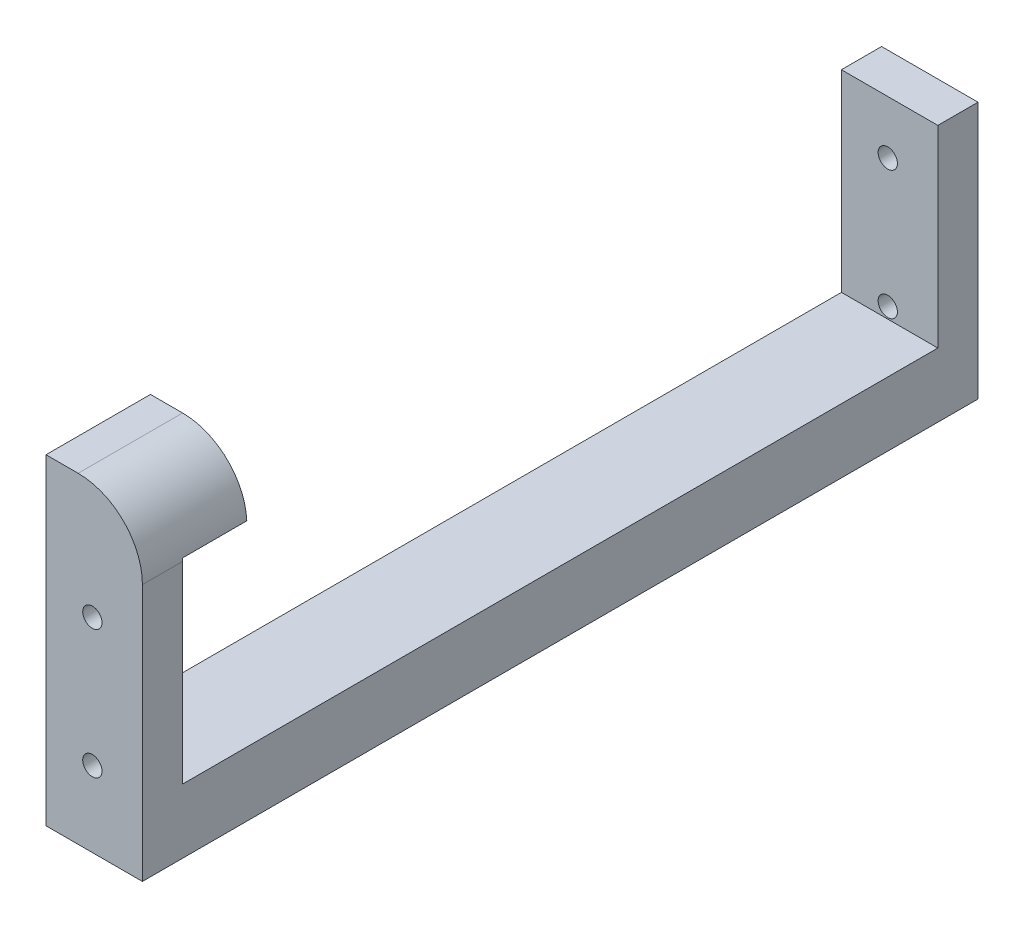
SolidWorks part; units mm, degrees
ref_plane "Front Plane" through (0, 0, 0) normal (0, 0, 1) x (1, 0, 0)
ref_plane "Top Plane" through (0, 0, 0) normal (0, 1, 0) x (1, 0, 0)
ref_plane "Right Plane" through (0, 0, 0) normal (1, 0, 0) x (0, 0, -1)
sketch "Sketch1" plane through (0, 0, 0) normal (0, 0, 1) x (1, 0, 0)
  line L1 (-7.5, 25) -> (7.5, 25)
  line L2 (-7.5, 25) -> (-7.5, -15)
  line L3 (-7.5, -15) -> (7.5, -15)
  line L4 (7.5, 25) -> (7.5, -15)
  dimension "D1" = 15
  dimension "D2" = 40
  dimension "D3" = 7.5
  dimension "D4" = 15
extrude "Boss-Extrude1" add sketch "Sketch1" along normal blind 130
sketch "Sketch2" plane through (0, 25, 0) normal (0, 1, 0) x (1, 0, 0)
  line L0 (-7.5, -130) -> (-7.5, 0) construction
  line L1 (-7.5, -6.25) -> (7.5, -6.25)
  line L2 (-7.5, -6.25) -> (-7.5, -123.75)
  line L3 (-7.5, -123.75) -> (7.5, -123.75)
  line L4 (7.5, -6.25) -> (7.5, -123.75)
  line L5 (7.5, -130) -> (7.5, 0) construction
  line L6 (7.5, -130) -> (-7.5, -130) construction
  dimension "1" = 117.5
  dimension "6.25" = 6.25
extrude "Cut-Extrude1" cut sketch "Sketch2" against normal blind 30
sketch "Sketch3" plane through (0, 0, 0) normal (0, 0, -1) x (-1, 0, 0)
  circle A0 centre (0.2894, 16.7166) radius 1.5
  circle A1 centre (0.2894, -3.2834) radius 1.5
  dimension "D2" = 3
  dimension "D3" = 3
  dimension "D1" = 20
extrude "Cut-Extrude2" cut sketch "Sketch3" against normal through all both and the other way through all
sketch "Sketch4" plane through (0, 25, 0) normal (0, 1, 0) x (1, 0, 0)
  line L1 (-7.5, 0) -> (7.5, 0)
  line L2 (-7.5, 0) -> (-7.5, -6.25)
  line L3 (-7.5, -6.25) -> (7.5, -6.25)
  line L4 (7.5, 0) -> (7.5, -6.25)
  line L5 (-7.5, -123.75) -> (7.5, -123.75)
  line L6 (-7.5, -123.75) -> (-7.5, -130)
  line L7 (-7.5, -130) -> (7.5, -130)
  line L8 (7.5, -123.75) -> (7.5, -130)
extrude "Boss-Extrude2" add sketch "Sketch4" along normal blind 10
sketch "Sketch5" plane through (0, 0, 123.75) normal (0, 0, -1) x (-1, 0, 0)
  line L0 (7.5, 35) -> (7.5, -15) construction
  line L1 (-7.5, 35) -> (7.5, 35)
  line L2 (-7.5, 35) -> (-7.5, 25.4598)
  line L3 (-7.5, 25.4598) -> (7.5, 25.4598)
  line L4 (7.5, 35) -> (7.5, 25.4598)
extrude "Boss-Extrude3" add sketch "Sketch5" along normal blind 10
sketch "Sketch6" plane through (0, 0, 6.25) normal (0, 0, 1) x (1, 0, 0)
  line L4 (7.5, 25.4598) -> (7.5, 35)
  line L5 (-7.5, 25.4598) -> (7.5, 25.4598)
  line L6 (-7.5, 35) -> (-7.5, 25.4598)
  line L7 (7.5, 35) -> (-7.5, 35)
  line L8 (7.5, 25.4598) -> (7.5, 35)
  line L9 (-7.5, 25.4598) -> (7.5, 25.4598)
  line L10 (-7.5, 35) -> (-7.5, 25.4598)
  line L11 (7.5, 35) -> (-7.5, 35)
  dimension "D1" = 0
fillet "Fillet1" radius 10 3 edges at (7.5, 25.4598, 118.75) (7.5, 35, 121.875) (7.5, 35, 3.125)
sketch "Sketch7" plane through (0, 35, 0) normal (0, 1, 0) x (1, 0, 0)
  line L1 (-7.5, 0) -> (7.5, 0)
  line L2 (-7.5, 0) -> (-7.5, -6.25)
  line L3 (-7.5, -6.25) -> (7.5, -6.25)
  line L4 (7.5, 0) -> (7.5, -6.25)
extrude "Cut-Extrude3" cut sketch "Sketch7" against normal blind 10
